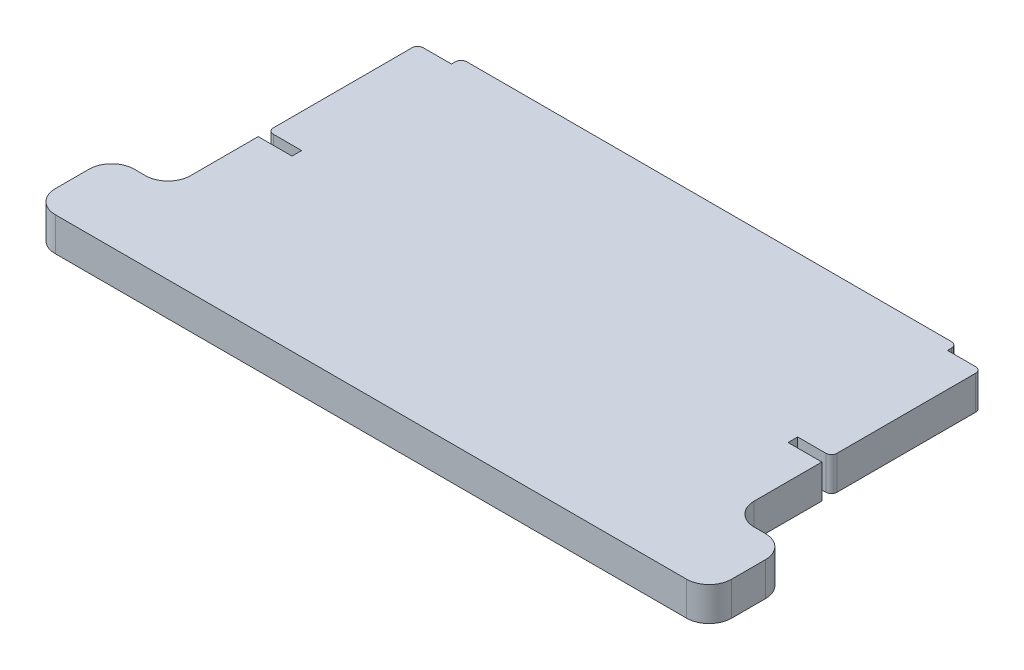
SolidWorks part; units mm, degrees
material "Commercially Pure CP-Ti UNS R50400 (SS)"
ref_plane "Front Plane" through (0, 0, 0) normal (0, 0, 1) x (1, 0, 0)
ref_plane "Top Plane" through (0, 0, 0) normal (0, 1, 0) x (1, 0, 0)
ref_plane "Right Plane" through (0, 0, 0) normal (1, 0, 0) x (0, 0, -1)
sketch "Sketch1" plane through (0, 0, 0) normal (0, 1, 0) x (1, 0, 0)
  line L0 (-25, -15) -> (-30, -15)
  line L1 (-25, -15) -> (25, -15)
  line L2 (-25, -15) -> (-25, 15) construction
  line L3 (-25, 15) -> (25, 15)
  line L4 (25, -15) -> (25, 15) construction
  line L5 (-25, -15) -> (25, 15) construction
  line L6 (-25, 15) -> (25, -15) construction
  line L7 (-30, -15) -> (-30, -8)
  line L8 (-30, -8) -> (-25, -8)
  line L9 (-25, -8) -> (-25, 15)
  line L10 (25, 15) -> (25, -8)
  line L11 (25, -8) -> (30, -8)
  line L12 (30, -8) -> (30, -15)
  line L13 (30, -15) -> (25, -15)
  point P0 (0, 0)
  dimension "D1" = 30
  dimension "D2" = 50
  dimension "D3" = 7
  dimension "D4" = 5
extrude "Boss-Extrude1" add sketch "Sketch1" along normal mid plane 3
sketch "Sketch2" plane through (0, 1.5, 0) normal (0, 1, 0) x (1, 0, 0)
  line L0 (-25, 15) -> (-25, -8) construction
  line L1 (25, 15) -> (-25, 15) construction
  line L2 (-25, 14.1468) -> (-22, 14.1468)
  line L3 (-22, 14.1468) -> (-22, 15)
  line L4 (-22, 15) -> (-25, 15)
  line L5 (-25, 0.8532) -> (-22, 0.8532)
  line L6 (-22, 0.8532) -> (-22, 0)
  line L7 (-22, 0) -> (-25, 0)
  line L8 (0, 0) -> (0, 50000) construction
  line L9 (22, 0.8532) -> (22, 0)
  line L10 (25, 0.8532) -> (22, 0.8532)
  line L11 (25, 14.1468) -> (22, 14.1468)
  line L12 (22, 14.1468) -> (22, 15)
  line L13 (22, 15) -> (25, 15)
  line L14 (22, 0) -> (25, 0)
  arc A0 (-25, 15) -> (-25, 0) centre (-22.2161, 7.5) ccw
  arc A1 (-25, 14.1468) -> (-25, 0.8532) centre (-22.2161, 7.5) ccw
  arc A2 (25, 14.1468) -> (25, 0.8532) centre (22.2161, 7.5) cw
  arc A3 (25, 15) -> (25, 0) centre (22.2161, 7.5) cw
  dimension "D1" = 8
  dimension "D3" = 0.7937
  dimension "D2" = 15
  dimension "D4" = 3
extrude "Cut-Extrude1" cut sketch "Sketch2" against normal through all both and the other way through all
fillet "Fillet1" radius 2 6 edges at (25, 0, 8) (30, 0, 8) (30, 0, 15) (-30, 0, 15) (-30, 0, 8) (-25, 0, 8)
fillet "Fillet2" radius 0.5 6 edges at (-22, 0, -15) (22, 0, -15)
